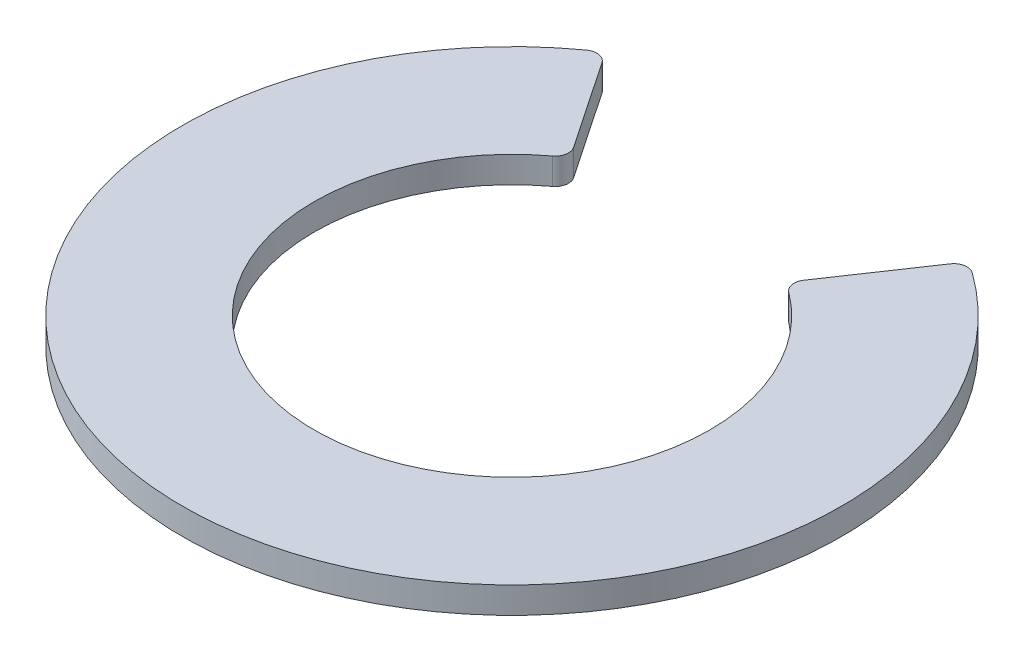
SolidWorks part; units mm, degrees
ref_plane "Front Plane" through (0, 0, 0) normal (0, 0, 1) x (1, 0, 0)
ref_plane "Top Plane" through (0, 0, 0) normal (0, 1, 0) x (1, 0, 0)
ref_plane "Right Plane" through (0, 0, 0) normal (1, 0, 0) x (0, 0, -1)
sketch "Sketch1" plane through (0, 0, 0) normal (0, 1, 0) x (1, 0, 0)
  line L0 (-1.3205, 2.0029) -> (-0.8725, 1.3394)
  line L1 (1.3205, 2.0029) -> (0.8725, 1.3394)
  arc A0 (-0.8956, 1.2033) -> (0.8956, 1.2033) centre (0, 0) ccw
  arc A1 (-1.4619, 2.028) -> (1.4619, 2.028) centre (0, 0) ccw
  arc A2 (1.4619, 2.028) -> (1.3205, 2.0029) centre (1.4034, 1.9469) ccw
  arc A3 (0.8725, 1.3394) -> (0.8956, 1.2033) centre (0.9553, 1.2835) ccw
  arc A4 (-0.8725, 1.3394) -> (-0.8956, 1.2033) centre (-0.9553, 1.2835) cw
  arc A5 (-1.3205, 2.0029) -> (-1.4619, 2.028) centre (-1.4034, 1.9469) ccw
  point P8 (1.377, 2.0866)
  point P11 (0.8173, 1.2578)
  point P14 (-0.8173, 1.2578)
  point P17 (-1.377, 2.0866)
  dimension "D1" = 1.5
  dimension "D2" = 2.5
  dimension "D3" = 0.1
extrude "Boss-Extrude1" add sketch "Sketch1" along normal blind 0.2
